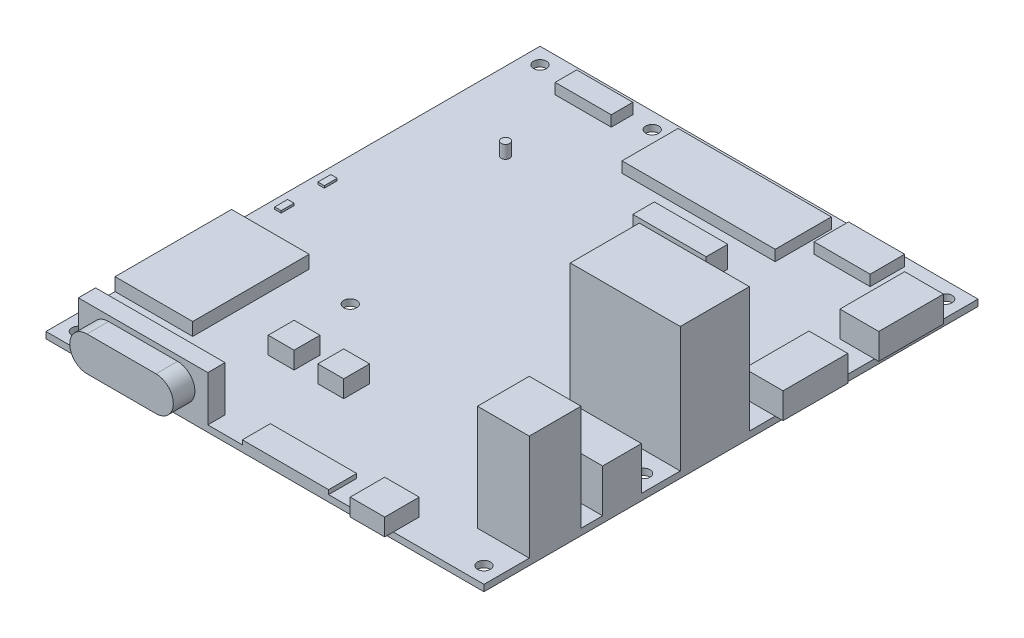
SolidWorks part; units mm, degrees
ref_plane "Front Plane" through (0, 0, 0) normal (0, 0, 1) x (1, 0, 0)
ref_plane "Top Plane" through (0, 0, 0) normal (0, 1, 0) x (1, 0, 0)
ref_plane "Right Plane" through (0, 0, 0) normal (1, 0, 0) x (0, 0, -1)
sketch "Sketch1" plane through (0, 0, 0) normal (0, 1, 0) x (1, 0, 0)
  line L1 (-50.75, -57.25) -> (50.75, -57.25)
  line L2 (-50.75, -57.25) -> (-50.75, 57.25)
  line L3 (-50.75, 57.25) -> (50.75, 57.25)
  line L4 (50.75, -57.25) -> (50.75, 57.25)
  line L5 (-50.75, -57.25) -> (50.75, 57.25) construction
  line L6 (-50.75, 57.25) -> (50.75, -57.25) construction
  point P0 (0, 0)
  dimension "D1" = 114.5
  dimension "D2" = 101.5
extrude "trükkplaat" add sketch "Sketch1" along normal blind 1.5
sketch "Sketch2" plane through (0, 1.5, 0) normal (0, 1, 0) x (1, 0, 0)
  line L1 (47, -53.5) -> (-47, -53.5) construction
  line L2 (47, -53.5) -> (47, 53.5) construction
  line L3 (47, 53.5) -> (-47, 53.5) construction
  line L4 (-47, -53.5) -> (-47, 53.5) construction
  line L5 (47, -53.5) -> (-47, 53.5) construction
  line L6 (47, 53.5) -> (-47, -53.5) construction
  line L7 (47, -16.5) -> (-21, -16.5) construction
  line L8 (47, -16.5) -> (47, 53.5) construction
  line L9 (47, 53.5) -> (-21, 53.5) construction
  line L10 (-21, -16.5) -> (-21, 53.5) construction
  line L11 (47, -16.5) -> (-21, 53.5) construction
  line L12 (47, 53.5) -> (-21, -16.5) construction
  circle A0 centre (-47, 53.5) radius 1.5
  circle A1 centre (47, 53.5) radius 1.5
  circle A2 centre (47, -53.5) radius 1.5
  circle A3 centre (-47, -53.5) radius 1.5
  circle A4 centre (-21, 53.5) radius 1.5
  circle A5 centre (-21, -16.5) radius 1.5
  circle A6 centre (47, -16.5) radius 1.5
  point P0 (0, 0)
  point P10 (13, 18.5)
  dimension "D3" = 3
  dimension "D1" = 94
  dimension "D2" = 107
  dimension "D4" = 68
  dimension "D5" = 70
extrude "augud" cut sketch "Sketch2" against normal blind 1.5
sketch "Sketch3" plane through (0, 1.5, 0) normal (0, 1, 0) x (1, 0, 0)
  line L0 (50.75, 57.25) -> (-50.75, 57.25) construction
  line L1 (19.75, 41.25) -> (-15.75, 41.25)
  line L2 (19.75, 41.25) -> (19.75, 54.25)
  line L3 (19.75, 54.25) -> (-15.75, 54.25)
  line L4 (-15.75, 41.25) -> (-15.75, 54.25)
  line L5 (19.75, 41.25) -> (-15.75, 54.25) construction
  line L6 (19.75, 54.25) -> (-15.75, 41.25) construction
  line L7 (50.75, -57.25) -> (50.75, 57.25) construction
  point P0 (2, 47.75)
  dimension "D1" = 35.5
  dimension "D2" = 13
  dimension "D3" = 3
  dimension "D4" = 31
extrude "exp. conn. A/B" add sketch "Sketch3" along normal blind 2.5
sketch "Sketch4" plane through (0, 1.5, 0) normal (0, 1, 0) x (1, 0, 0)
  line L0 (19.75, 41.25) -> (19.75, 54.25) construction
  line L1 (35.75, 47.25) -> (22.75, 47.25)
  line L2 (35.75, 47.25) -> (35.75, 55.25)
  line L3 (35.75, 55.25) -> (22.75, 55.25)
  line L4 (22.75, 47.25) -> (22.75, 55.25)
  line L5 (35.75, 47.25) -> (22.75, 55.25) construction
  line L6 (35.75, 55.25) -> (22.75, 47.25) construction
  line L7 (50.75, 57.25) -> (-50.75, 57.25) construction
  point P0 (29.25, 51.25)
  dimension "D1" = 13
  dimension "D2" = 8
  dimension "D3" = 3
  dimension "D4" = 2
extrude "LCD conn. A/B" add sketch "Sketch4" along normal blind 2.5
sketch "Sketch5" plane through (0, 1.5, 0) normal (0, 1, 0) x (1, 0, 0)
  line L0 (-50.75, 57.25) -> (-50.75, -57.25) construction
  line L1 (-39.25, 54.25) -> (-26.25, 54.25)
  line L2 (-39.25, 54.25) -> (-39.25, 49.25)
  line L3 (-39.25, 49.25) -> (-26.25, 49.25)
  line L4 (-26.25, 54.25) -> (-26.25, 49.25)
  line L5 (-39.25, 54.25) -> (-26.25, 49.25) construction
  line L6 (-39.25, 49.25) -> (-26.25, 54.25) construction
  line L7 (50.75, 57.25) -> (-50.75, 57.25) construction
  point P0 (-32.75, 51.75)
  dimension "D1" = 13
  dimension "D2" = 5
  dimension "D3" = 11.5
  dimension "D4" = 3
extrude "WIFI/BT" add sketch "Sketch5" along normal blind 2.5
sketch "Sketch6" plane through (0, 1.5, 0) normal (0, 1, 0) x (1, 0, 0)
  line L0 (-15.75, 41.25) -> (19.75, 41.25) construction
  line L1 (-1.25, 29.25) -> (15.75, 29.25)
  line L2 (-1.25, 29.25) -> (-1.25, 34.25)
  line L3 (-1.25, 34.25) -> (15.75, 34.25)
  line L4 (15.75, 29.25) -> (15.75, 34.25)
  line L5 (-1.25, 29.25) -> (15.75, 34.25) construction
  line L6 (-1.25, 34.25) -> (15.75, 29.25) construction
  line L7 (50.75, -57.25) -> (50.75, 57.25) construction
  point P0 (7.25, 31.75)
  dimension "D1" = 17
  dimension "D2" = 5
  dimension "D3" = 7
  dimension "D4" = 52
extrude "JTAG" add sketch "Sketch6" along normal blind 5
sketch "Sketch7" plane through (0, 1.5, 0) normal (0, 1, 0) x (1, 0, 0)
  line L0 (50.75, 57.25) -> (-50.75, 57.25) construction
  line L1 (42.75, 48.25) -> (51.75, 48.25)
  line L2 (42.75, 48.25) -> (42.75, 33.25)
  line L3 (42.75, 33.25) -> (51.75, 33.25)
  line L4 (51.75, 48.25) -> (51.75, 33.25)
  line L5 (42.75, 48.25) -> (51.75, 33.25) construction
  line L6 (42.75, 33.25) -> (51.75, 48.25) construction
  line L7 (50.75, -57.25) -> (50.75, 57.25) construction
  line L8 (43.5689, 25.25) -> (52.5689, 25.25)
  line L9 (43.5689, 25.25) -> (43.5689, 10.25)
  line L10 (43.5689, 10.25) -> (52.5689, 10.25)
  line L11 (52.5689, 25.25) -> (52.5689, 10.25)
  line L12 (43.5689, 25.25) -> (52.5689, 10.25) construction
  line L13 (43.5689, 10.25) -> (52.5689, 25.25) construction
  point P0 (47.25, 40.75)
  point P10 (48.0689, 17.75)
  dimension "D1" = 9
  dimension "D2" = 15
  dimension "D3" = 9
  dimension "D4" = 8
  dimension "D6" = 8
  dimension "D5" = 2
extrude "HDMI A/B" add sketch "Sketch7" along normal blind 6
sketch "Sketch8" plane through (0, 1.5, 0) normal (0, 1, 0) x (1, 0, 0)
  line L0 (50.75, -57.25) -> (50.75, 10.25) construction
  line L1 (25.25, 4.25) -> (50.75, 4.25)
  line L2 (25.25, 4.25) -> (25.25, -11.75)
  line L3 (25.25, -11.75) -> (50.75, -11.75)
  line L4 (50.75, 4.25) -> (50.75, -11.75)
  line L5 (25.25, 4.25) -> (50.75, -11.75) construction
  line L6 (25.25, -11.75) -> (50.75, 4.25) construction
  line L7 (43.5689, 10.25) -> (50.75, 10.25) construction
  point P0 (38, -3.75)
  dimension "D1" = 25.5
  dimension "D2" = 16
  dimension "D3" = 6
extrude "USB/Ethernet" add sketch "Sketch8" along normal blind 29
sketch "Sketch9" plane through (0, 1.5, 0) normal (0, 1, 0) x (1, 0, 0)
  line L0 (25.25, -11.75) -> (50.75, -11.75) construction
  line L1 (50.75, -20.75) -> (36.75, -20.75)
  line L2 (50.75, -20.75) -> (50.75, -29.75)
  line L3 (50.75, -29.75) -> (36.75, -29.75)
  line L4 (36.75, -20.75) -> (36.75, -29.75)
  line L5 (50.75, -20.75) -> (36.75, -29.75) construction
  line L6 (50.75, -29.75) -> (36.75, -20.75) construction
  line L7 (50.75, -57.25) -> (50.75, -11.75) construction
  point P0 (43.75, -25.25)
  dimension "D1" = 9
  dimension "D2" = 14
  dimension "D3" = 9
extrude "5V in" add sketch "Sketch9" along normal blind 10
sketch "Sketch10" plane through (0, 1.5, 0) normal (0, 1, 0) x (1, 0, 0)
  line L0 (36.75, -29.75) -> (50.75, -29.75) construction
  line L1 (38.75, -34.75) -> (50.75, -34.75)
  line L2 (38.75, -34.75) -> (38.75, -46.75)
  line L3 (38.75, -46.75) -> (50.75, -46.75)
  line L4 (50.75, -34.75) -> (50.75, -46.75)
  line L5 (38.75, -34.75) -> (50.75, -46.75) construction
  line L6 (38.75, -46.75) -> (50.75, -34.75) construction
  line L7 (50.75, -57.25) -> (50.75, -29.75) construction
  point P0 (44.75, -40.75)
  dimension "D1" = 12
  dimension "D2" = 12
  dimension "D3" = 5
extrude "Headphone" add sketch "Sketch10" along normal blind 24.5
sketch "Sketch11" plane through (0, 1.5, 0) normal (0, 1, 0) x (1, 0, 0)
  line L0 (50.75, -57.25) -> (50.75, -46.75) construction
  line L1 (21.75, -51.25) -> (29.75, -51.25)
  line L2 (21.75, -51.25) -> (21.75, -59.25)
  line L3 (21.75, -59.25) -> (29.75, -59.25)
  line L4 (29.75, -51.25) -> (29.75, -59.25)
  line L5 (21.75, -51.25) -> (29.75, -59.25) construction
  line L6 (21.75, -59.25) -> (29.75, -51.25) construction
  line L7 (-50.75, -57.25) -> (50.75, -57.25) construction
  point P0 (25.75, -55.25)
  dimension "D1" = 8
  dimension "D2" = 8
  dimension "D3" = 29
  dimension "D4" = 6
extrude "mini-USB" add sketch "Sketch11" along normal blind 4
sketch "Sketch12" plane through (0, 1.5, 0) normal (0, 1, 0) x (1, 0, 0)
  line L0 (-50.75, -57.25) -> (21.75, -57.25) construction
  line L1 (-13.25, -53.25) -> (-43.25, -53.25)
  line L2 (-13.25, -53.25) -> (-13.25, -57.25)
  line L3 (-13.25, -57.25) -> (-43.25, -57.25)
  line L4 (-43.25, -53.25) -> (-43.25, -57.25)
  line L5 (-13.25, -53.25) -> (-43.25, -57.25) construction
  line L6 (-13.25, -57.25) -> (-43.25, -53.25) construction
  line L7 (29.75, -57.25) -> (29.75, -51.25) construction
  point P0 (-28.25, -55.25)
  dimension "D1" = 30
  dimension "D2" = 4
  dimension "D3" = 73
extrude "Boss-Extrude11" add sketch "Sketch12" along normal blind 10.5
sketch "Sketch13" plane through (0, 0, 57.25) normal (0, 0, 1) x (1, 0, 0)
  line L0 (-13.25, 12) -> (-43.25, 1.5) construction
  line L1 (-36.25, 6.75) -> (-20.25, 6.75) construction
  line L2 (-36.25, 10.75) -> (-20.25, 10.75)
  line L3 (-36.25, 2.75) -> (-20.25, 2.75)
  arc A0 (-36.25, 10.75) -> (-36.25, 2.75) centre (-36.25, 6.75) ccw
  arc A1 (-20.25, 2.75) -> (-20.25, 10.75) centre (-20.25, 6.75) ccw
  point P6 (-28.25, 6.75)
  dimension "D1" = 8
  dimension "D2" = 16
extrude "Boss-Extrude12" add sketch "Sketch13" along normal blind 5
sketch "Sketch14" plane through (0, 1.5, 0) normal (0, 1, 0) x (1, 0, 0)
  line L0 (-50.75, 57.25) -> (-50.75, -57.25) construction
  line L1 (-32.75, -41.25) -> (-50.75, -41.25)
  line L2 (-32.75, -41.25) -> (-32.75, -14.25)
  line L3 (-32.75, -14.25) -> (-50.75, -14.25)
  line L4 (-50.75, -41.25) -> (-50.75, -14.25)
  line L5 (-32.75, -41.25) -> (-50.75, -14.25) construction
  line L6 (-32.75, -14.25) -> (-50.75, -41.25) construction
  line L7 (-50.75, -57.25) -> (-43.25, -57.25) construction
  point P0 (-41.75, -27.75)
  dimension "D1" = 27
  dimension "D2" = 18
  dimension "D3" = 43
extrude "SD-card slot" add sketch "Sketch14" along normal blind 3
sketch "Sketch15" plane through (0, 1.5, 0) normal (0, 1, 0) x (1, 0, 0)
  line L0 (-50.75, 57.25) -> (-50.75, -14.25) construction
  line L1 (-48.75, -3.25) -> (-47.25, -3.25)
  line L2 (-48.75, -3.25) -> (-48.75, -6.25)
  line L3 (-48.75, -6.25) -> (-47.25, -6.25)
  line L4 (-47.25, -3.25) -> (-47.25, -6.25)
  line L5 (-48.75, -3.25) -> (-47.25, -6.25) construction
  line L6 (-48.75, -6.25) -> (-47.25, -3.25) construction
  line L7 (-50.75, -41.25) -> (-32.75, -41.25) construction
  line L8 (-48.75, 6.75) -> (-47.25, 6.75)
  line L9 (-48.75, 6.75) -> (-48.75, 3.75)
  line L10 (-48.75, 3.75) -> (-47.25, 3.75)
  line L11 (-47.25, 6.75) -> (-47.25, 3.75)
  line L12 (-48.75, 6.75) -> (-47.25, 3.75) construction
  line L13 (-48.75, 3.75) -> (-47.25, 6.75) construction
  point P0 (-48, -4.75)
  point P10 (-48, 5.25)
  dimension "D1" = 3
  dimension "D2" = 1.5
  dimension "D3" = 3.5
  dimension "D4" = 38
  dimension "D6" = 13
  dimension "D5" = 2
extrude "status LED" add sketch "Sketch15" along normal blind 0.5
sketch "Sketch16" plane through (0, 1.5, 0) normal (0, 1, 0) x (1, 0, 0)
  line L0 (-50.75, -57.25) -> (-43.25, -57.25) construction
  line L1 (-8.75, -30.25) -> (-2.75, -30.25)
  line L2 (-8.75, -30.25) -> (-8.75, -36.25)
  line L3 (-8.75, -36.25) -> (-2.75, -36.25)
  line L4 (-2.75, -30.25) -> (-2.75, -36.25)
  line L5 (-8.75, -30.25) -> (-2.75, -36.25) construction
  line L6 (-8.75, -36.25) -> (-2.75, -30.25) construction
  line L7 (-50.75, -41.25) -> (-50.75, -57.25) construction
  line L8 (-20.25, -30.25) -> (-14.25, -30.25)
  line L9 (-20.25, -30.25) -> (-20.25, -36.25)
  line L10 (-20.25, -36.25) -> (-14.25, -36.25)
  line L11 (-14.25, -30.25) -> (-14.25, -36.25)
  line L12 (-20.25, -30.25) -> (-14.25, -36.25) construction
  line L13 (-20.25, -36.25) -> (-14.25, -30.25) construction
  point P0 (-5.75, -33.25)
  point P10 (-17.25, -33.25)
  dimension "D1" = 6
  dimension "D2" = 6
  dimension "D3" = 27
  dimension "D4" = 48
  dimension "D6" = 17.5
  dimension "D5" = 2
extrude "PWRON_RESET/GPIO_121" add sketch "Sketch16" along normal blind 4
sketch "Sketch17" plane through (0, 1.5, 0) normal (0, 1, 0) x (1, 0, 0)
  line L0 (-13.25, -57.25) -> (21.75, -57.25) construction
  line L1 (14.75, -50.75) -> (-5.25, -50.75)
  line L2 (14.75, -50.75) -> (14.75, -57.25)
  line L3 (14.75, -57.25) -> (-5.25, -57.25)
  line L4 (-5.25, -50.75) -> (-5.25, -57.25)
  line L5 (14.75, -50.75) -> (-5.25, -57.25) construction
  line L6 (14.75, -57.25) -> (-5.25, -50.75) construction
  line L7 (50.75, -57.25) -> (50.75, -46.75) construction
  point P0 (4.75, -54)
  dimension "D1" = 20
  dimension "D2" = 6.5
  dimension "D3" = 36
extrude "camera conn." add sketch "Sketch17" along normal blind 1
sketch "Sketch18" plane through (0, 1.5, 0) normal (0, 1, 0) x (1, 0, 0)
  line L0 (50.75, 57.25) -> (-50.75, 57.25) construction
  line L1 (-50.75, 57.25) -> (-50.75, -14.25) construction
  circle A0 centre (-32.75, 31.25) radius 1
  dimension "D2" = 18
  dimension "D3" = 2
  dimension "D1" = 26
extrude "WIFI?/BT? antenna" add sketch "Sketch18" along normal blind 3
